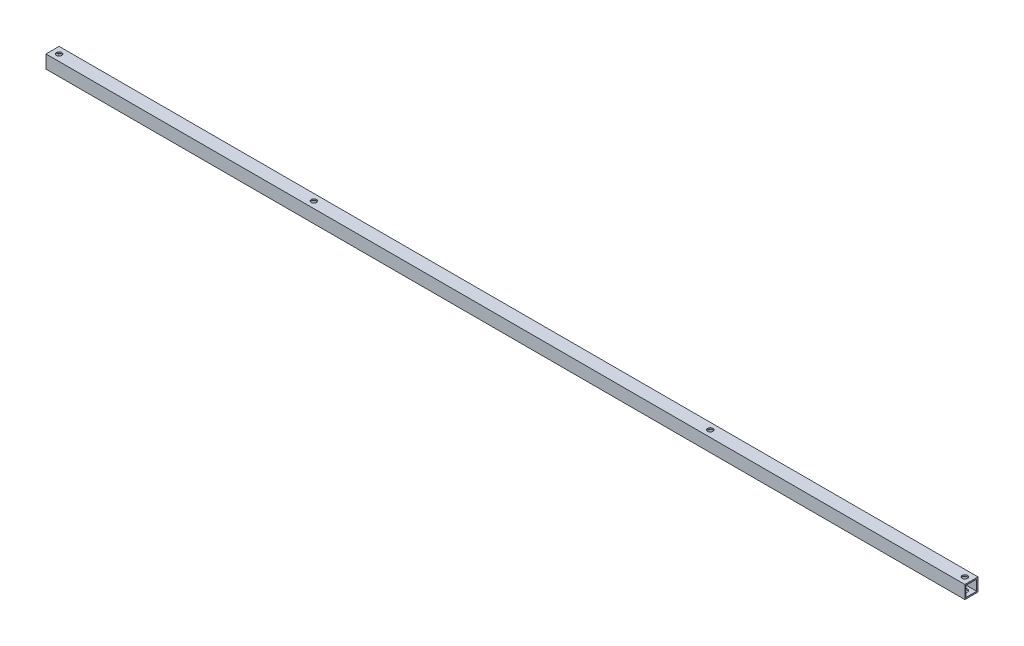
SolidWorks part; units mm, degrees
material "5052-H34"
ref_plane "正面" through (0, 0, 0) normal (0, 0, 1) x (1, 0, 0)
ref_plane "平面" through (0, 0, 0) normal (0, 1, 0) x (1, 0, 0)
ref_plane "右側面" through (0, 0, 0) normal (1, 0, 0) x (0, 0, -1)
sketch "ｽｹｯﾁ1" plane through (0, 0, 0) normal (1, 0, 0) x (0, 0, -1)
  line L1 (-5, 5) -> (5, 5)
  line L2 (-5, 5) -> (-5, -5)
  line L3 (-5, -5) -> (5, -5)
  line L4 (5, 5) -> (5, -5)
  line L5 (-5, 5) -> (5, -5) construction
  line L6 (-5, -5) -> (5, 5) construction
  point P0 (0, 0)
  dimension "D1" = 10
  dimension "D2" = 10
extrude "押し出し-薄板1" add sketch "ｽｹｯﾁ1" along normal blind 700 thin
sketch "ｽｹｯﾁ2" plane through (0, 5, 0) normal (0, 1, 0) x (1, 0, 0)
  line L0 (350, 5) -> (350, -5) construction
  line L1 (700, 5) -> (0, 5) construction
  line L2 (700, -5) -> (0, -5) construction
  line L3 (700, 0) -> (695, 0) construction
  line L4 (700, 5) -> (700, -5) construction
  line L5 (350, 0) -> (501, 0) construction
  circle A0 centre (695, 0) radius 2
  circle A1 centre (5, 0) radius 2
  circle A2 centre (501, 0) radius 2
  circle A3 centre (199, 0) radius 2
  dimension "D2" = 4
  dimension "D3" = 4
  dimension "D1" = 5
  dimension "D4" = 302
extrude "ｶｯﾄ - 押し出し1" cut sketch "ｽｹｯﾁ2" against normal through all
